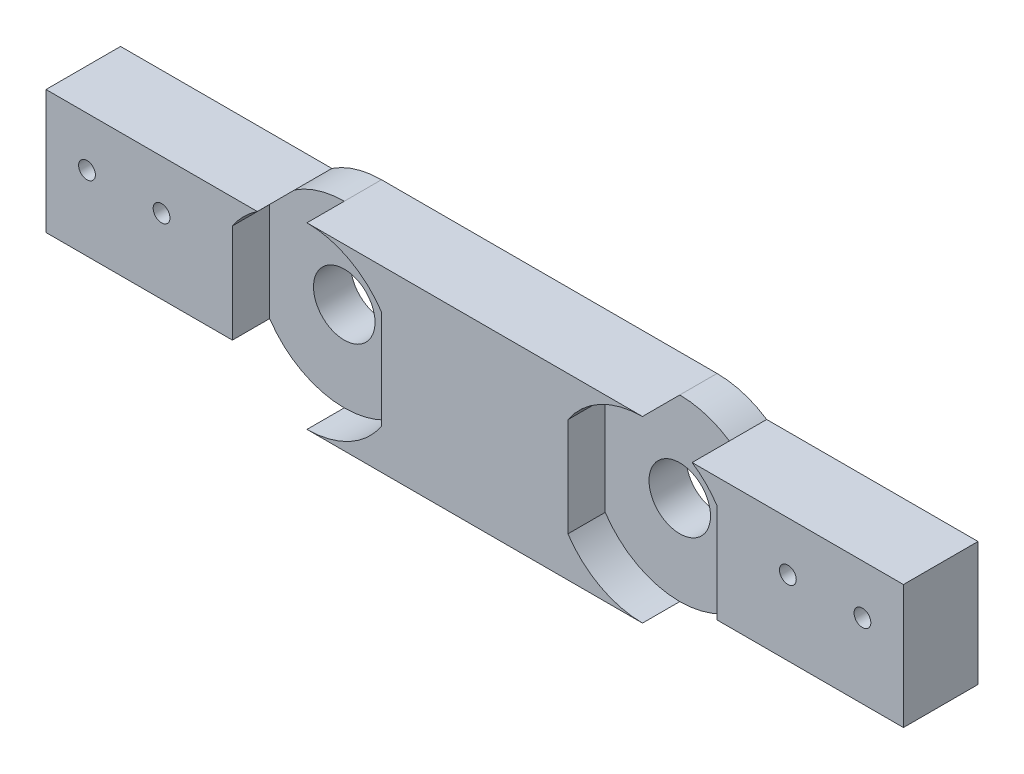
SolidWorks part; units mm, degrees
ref_plane "정면" through (0, 0, 0) normal (0, 0, 1) x (1, 0, 0)
ref_plane "윗면" through (0, 0, 0) normal (0, 1, 0) x (1, 0, 0)
ref_plane "우측면" through (0, 0, 0) normal (1, 0, 0) x (0, 0, -1)
sketch "스케치1" plane through (0, 0, 0) normal (0, 0, 1) x (1, 0, 0)
  line L1 (-20, 24) -> (110, 24)
  line L2 (-20, 24) -> (-20, -24)
  line L3 (-20, -24) -> (110, -24)
  line L4 (110, 24) -> (110, -24)
  line L5 (-20, 24) -> (110, -24) construction
  line L6 (-20, -24) -> (110, 24) construction
  circle A0 centre (0, 0) radius 8.25
  circle A1 centre (90, 0) radius 8.25
  point P3 (45, 0)
  dimension "D1" = 16.5
  dimension "D5" = 16.5
  dimension "D2" = 48
  dimension "D3" = 0
  dimension "D4" = 20
  dimension "D6" = 20
  dimension "D7" = 24
  dimension "D8" = 90
extrude "보스-돌출1" add sketch "스케치1" along normal blind 10
sketch "스케치4" plane through (0, 0, 10) normal (0, 0, 1) x (1, 0, 0)
  line L0 (-20, 24) -> (-20, -24) construction
  line L1 (-20, -24) -> (110, -24) construction
  line L2 (-20, -13.2665) -> (-20, -24)
  line L3 (-20, -24) -> (0, -24)
  line L4 (45, 24) -> (45, -24) construction
  line L5 (110, 24) -> (-20, 24) construction
  line L6 (-20, 0) -> (110, 0) construction
  line L7 (110, -24) -> (110, 24) construction
  line L8 (-20, 24) -> (0, 24)
  line L9 (-20, 13.2665) -> (-20, 24)
  line L10 (110, -24) -> (90, -24)
  line L11 (110, -13.2665) -> (110, -24)
  line L12 (110, 13.2665) -> (110, 24)
  line L13 (110, 24) -> (90, 24)
  arc A0 (-20, -13.2665) -> (0, -24) centre (0, 0) ccw
  arc A1 (-20, 13.2665) -> (0, 24) centre (0, 0) cw
  arc A2 (110, -13.2665) -> (90, -24) centre (90, 0) cw
  arc A3 (110, 13.2665) -> (90, 24) centre (90, 0) ccw
  line M7 (110, -24) -> (110, 24)
  line M8 (110, 24) -> (-20, 24)
  line M9 (-20, 24) -> (-20, -24)
  line M10 (-20, -24) -> (110, -24)
  dimension "D1" = 24
extrude "컷-돌출1" cut sketch "스케치4" against normal blind 10 contours A1 M9 M8 | A0 M9 M10 | A2 M7 M10 | A3 M7 M8
sketch "스케치5" plane through (0, 0, 10) normal (0, 0, 1) x (1, 0, 0)
  line L0 (20, -13.2665) -> (20, 13.2665)
  line L1 (-16.315, 0) -> (110, 0) construction
  line L2 (110, -13.2665) -> (110, 13.2665) construction
  line L3 (45, 24) -> (45, -24) construction
  line L4 (90, 24) -> (0, 24) construction
  line L5 (0, -24) -> (90, -24) construction
  line L6 (70, -13.2665) -> (70, 13.2665)
  line L7 (0, 24) -> (90, 24)
  line L8 (0, -24) -> (90, -24)
  line L9 (-20, 13.2665) -> (-20, -13.2665) construction
  arc A0 (0, -24) -> (20, -13.2665) centre (0, 0) ccw
  arc A1 (90, -24) -> (70, -13.2665) centre (90, 0) cw
  arc A2 (90, 24) -> (70, 13.2665) centre (90, 0) ccw
  arc A3 (0, 24) -> (20, 13.2665) centre (0, 0) cw
  point P23 (70, 0)
  point P25 (20, 0)
  dimension "D1" = 0
extrude "보스-돌출2" add sketch "스케치5" along normal blind 10
sketch "스케치6" plane through (110, 0, 0) normal (1, 0, 0) x (0, 0, -1)
  line L1 (-10, -13.2665) -> (0, -13.2665)
  line L2 (-10, -13.2665) -> (-10, 13.2665)
  line L3 (-10, 13.2665) -> (0, 13.2665)
  line L4 (0, -13.2665) -> (0, 13.2665)
extrude "보스-돌출3" add sketch "스케치6" along normal blind 50
sketch "스케치7" plane through (0, 0, 10) normal (0, 0, 1) x (1, 0, 0)
  line L1 (160, 13.2665) -> (110, 13.2665)
  line L2 (160, 13.2665) -> (160, -13.2665)
  line L3 (160, -13.2665) -> (110, -13.2665)
  line L4 (110, 13.2665) -> (110, -13.2665)
extrude "보스-돌출4" add sketch "스케치7" along normal blind 10
ref_plane "평면1" through (45, 0, 0) normal (-1, 0, 0) x (0, 0, 1)
mirror "대칭 복사2" about plane through (45, 0, 0) normal (-1, 0, 0) of "보스-돌출4", "보스-돌출3"
ref_plane "평면2" through (0, 0, 30) normal (0, 0, 1) x (1, 0, 0)
hole_wizard "M4 남비 머리 나사용 카운터보어1" positions "스케치12" profile "스케치11" counterbore size "M4" standard "ISO"
sketch "스케치12" plane through (0, 0, 30) normal (0, 0, 1) x (1, 0, 0)
  line L0 (-20, -13.2665) -> (-70, -13.2665) construction
  line L2 (-70, -13.2665) -> (-70, 13.2665) construction
  line L3 (-20, 13.2665) -> (-20, -13.2665) construction
  point P0 (-59, 6.7335)
  point P17 (-39, 6.7335)
  dimension "D1" = 20
  dimension "D2" = 19
  dimension "D3" = 11
  dimension "D4" = 20
sketch "스케치11" plane through (-59, 6.7335, 30) normal (1, 0, 0) x (0, -1, 0)
  line L0 (0, 0) -> (0, 31.3519)
  line L1 (0, 31.3519) -> (2.25, 30)
  line L2 (2.25, 30) -> (2.25, 3.1)
  line L3 (2.25, 3.1) -> (4.5, 3.1)
  line L4 (4.5, 3.1) -> (4.5, 0)
  line L5 (4.5, 0) -> (0, 0)
  line L10 (0, 31.3519) -> (-2.25, 30) construction
  line L11 (0, -6.35) -> (0, 107.95) construction
  dimension "구멍 지름" = 4.5
  dimension "구멍 깊이" = 30
  dimension "카운터보어 지름" = 9
  dimension "카운터보어 깊이" = 3.1
  dimension "드릴 각도" = 118
sketch "스케치14" plane through (0, 0, 20) normal (0, 0, 1) x (1, 0, 0)
  line L0 (-20, 13.2665) -> (-70, 13.2665)
  line L1 (-70, 13.2665) -> (-70, 19.9665)
  line L2 (-70, 19.9665) -> (-13.3169, 19.9665)
  arc A0 (0, 24) -> (-20, 13.2665) centre (0, 0) ccw construction
  arc A1 (-20, 13.2665) -> (-13.3169, 19.9665) centre (0, 0) cw
  line M7 (-20, 13.2665) -> (-70, 13.2665)
  dimension "D1" = 6.7
extrude "보스-돌출6" add sketch "스케치14" against normal through all contours A1 L2 L1 M7
ref_plane "평면3" through (45, 0, 0) normal (-1, 0, 0) x (0, 0, 1)
mirror "대칭 복사3" about plane through (45, 0, 0) normal (-1, 0, 0) of "보스-돌출6", "M4 남비 머리 나사용 카운터보어1"
